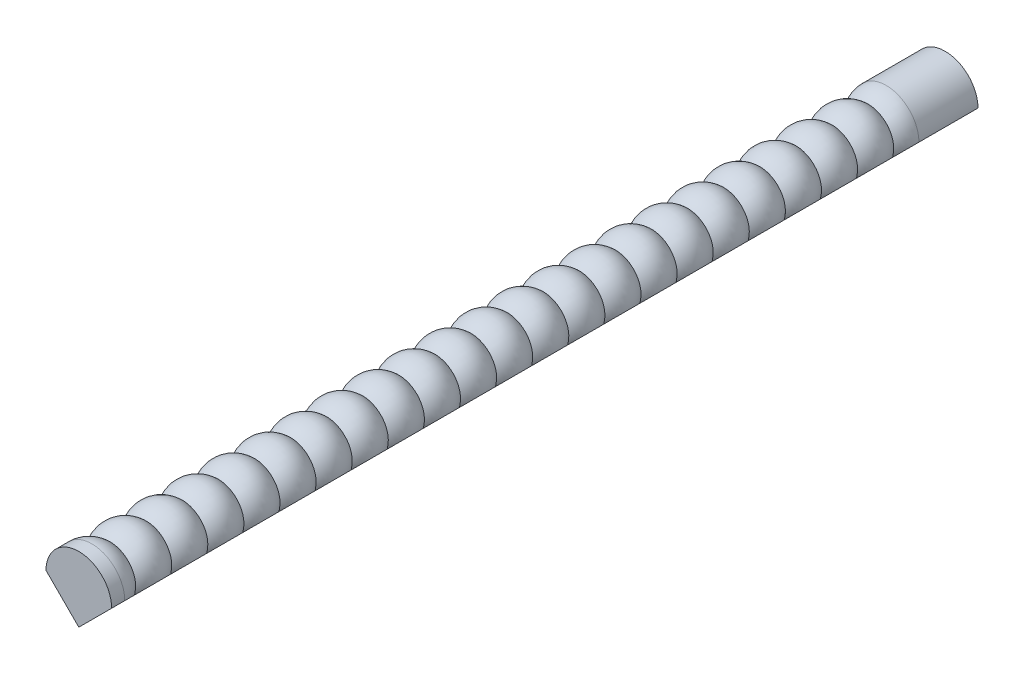
SolidWorks part; units mm, degrees
ref_plane "Front Plane" through (0, 0, 0) normal (0, 0, 1) x (1, 0, 0)
ref_plane "Top Plane" through (0, 0, 0) normal (0, 1, 0) x (1, 0, 0)
ref_plane "Right Plane" through (0, 0, 0) normal (1, 0, 0) x (0, 0, -1)
sketch "Sketch1" plane through (0, 0, 0) normal (1, 0, 0) x (0, 0, -1)
  line L0 (0, 0) -> (0, 5)
  line L1 (0, 5) -> (2, 5)
  line L2 (0, 0) -> (2, 0)
  line L3 (2, 0) -> (2, 1)
  line L4 (2, 1) -> (2, 3)
  line L5 (4, 1) -> (4.75, 1)
  line L6 (9.5, 1) -> (10.25, 1)
  line L7 (4.75, 1) -> (4.75, 3.9047) construction
  line L8 (10.25, 1) -> (10.25, 3.9047) construction
  line L9 (4.75, 1) -> (5.5, 1)
  line L10 (15, 1) -> (15.75, 1)
  line L11 (10.25, 1) -> (11, 1)
  line L12 (20.5, 1) -> (21.25, 1)
  line L13 (15.75, 1) -> (16.5, 1)
  line L14 (26, 1) -> (26.75, 1)
  line L15 (21.25, 1) -> (22, 1)
  line L16 (31.5, 1) -> (32.25, 1)
  line L17 (26.75, 1) -> (27.5, 1)
  line L18 (37, 1) -> (37.75, 1)
  line L19 (32.25, 1) -> (33, 1)
  line L20 (42.5, 1) -> (43.25, 1)
  line L21 (37.75, 1) -> (38.5, 1)
  line L22 (48, 1) -> (48.75, 1)
  line L23 (43.25, 1) -> (44, 1)
  line L24 (53.5, 1) -> (54.25, 1)
  line L25 (48.75, 1) -> (49.5, 1)
  line L26 (59, 1) -> (59.75, 1)
  line L27 (54.25, 1) -> (55, 1)
  line L28 (64.5, 1) -> (65.25, 1)
  line L29 (59.75, 1) -> (60.5, 1)
  line L30 (70, 1) -> (70.75, 1)
  line L31 (65.25, 1) -> (66, 1)
  line L32 (75.5, 1) -> (76.25, 1)
  line L33 (70.75, 1) -> (71.5, 1)
  line L34 (81, 1) -> (81.75, 1)
  line L35 (76.25, 1) -> (77, 1)
  line L36 (86.5, 1) -> (87.25, 1)
  line L37 (81.75, 1) -> (82.5, 1)
  line L38 (92, 1) -> (92.75, 1)
  line L39 (87.25, 1) -> (88, 1)
  line L40 (97.5, 1) -> (98.25, 1)
  line L41 (92.75, 1) -> (93.5, 1)
  line L42 (103, 1) -> (103.75, 1)
  line L43 (98.25, 1) -> (99, 1)
  line L44 (108.5, 1) -> (109.25, 1)
  line L45 (103.75, 1) -> (104.5, 1)
  line L46 (114, 1) -> (114.75, 1)
  line L47 (109.25, 1) -> (110, 1)
  line L48 (119.5, 1) -> (120.25, 1)
  line L49 (114.75, 1) -> (115.5, 1)
  line L50 (4.75, 3.9047) -> (10.25, 3.9047) construction
  line L51 (120.25, 1) -> (121, 1)
  line L52 (123, 3) -> (123, 1)
  line L53 (123, 1) -> (132, 1)
  line L54 (132, 1) -> (132, 5)
  line L55 (132, 5) -> (123, 5)
  arc A0 (2, 3) -> (4, 1) centre (2, 1) cw
  arc A1 (5.5, 1) -> (9.5, 1) centre (7.5, 1) cw
  arc A2 (4.75, 3.9047) -> (10.25, 3.9047) centre (7.5, 1) cw
  arc A3 (2, 5) -> (4.75, 3.9047) centre (2, 1) cw
  arc A4 (10.25, 3.9047) -> (15.75, 3.9047) centre (13, 1) cw
  arc A5 (11, 1) -> (15, 1) centre (13, 1) cw
  arc A6 (15.75, 3.9047) -> (21.25, 3.9047) centre (18.5, 1) cw
  arc A7 (16.5, 1) -> (20.5, 1) centre (18.5, 1) cw
  arc A8 (21.25, 3.9047) -> (26.75, 3.9047) centre (24, 1) cw
  arc A9 (22, 1) -> (26, 1) centre (24, 1) cw
  arc A10 (26.75, 3.9047) -> (32.25, 3.9047) centre (29.5, 1) cw
  arc A11 (27.5, 1) -> (31.5, 1) centre (29.5, 1) cw
  arc A12 (32.25, 3.9047) -> (37.75, 3.9047) centre (35, 1) cw
  arc A13 (33, 1) -> (37, 1) centre (35, 1) cw
  arc A14 (37.75, 3.9047) -> (43.25, 3.9047) centre (40.5, 1) cw
  arc A15 (38.5, 1) -> (42.5, 1) centre (40.5, 1) cw
  arc A16 (43.25, 3.9047) -> (48.75, 3.9047) centre (46, 1) cw
  arc A17 (44, 1) -> (48, 1) centre (46, 1) cw
  arc A18 (48.75, 3.9047) -> (54.25, 3.9047) centre (51.5, 1) cw
  arc A19 (49.5, 1) -> (53.5, 1) centre (51.5, 1) cw
  arc A20 (54.25, 3.9047) -> (59.75, 3.9047) centre (57, 1) cw
  arc A21 (55, 1) -> (59, 1) centre (57, 1) cw
  arc A22 (59.75, 3.9047) -> (65.25, 3.9047) centre (62.5, 1) cw
  arc A23 (60.5, 1) -> (64.5, 1) centre (62.5, 1) cw
  arc A24 (65.25, 3.9047) -> (70.75, 3.9047) centre (68, 1) cw
  arc A25 (66, 1) -> (70, 1) centre (68, 1) cw
  arc A26 (70.75, 3.9047) -> (76.25, 3.9047) centre (73.5, 1) cw
  arc A27 (71.5, 1) -> (75.5, 1) centre (73.5, 1) cw
  arc A28 (76.25, 3.9047) -> (81.75, 3.9047) centre (79, 1) cw
  arc A29 (77, 1) -> (81, 1) centre (79, 1) cw
  arc A30 (81.75, 3.9047) -> (87.25, 3.9047) centre (84.5, 1) cw
  arc A31 (82.5, 1) -> (86.5, 1) centre (84.5, 1) cw
  arc A32 (87.25, 3.9047) -> (92.75, 3.9047) centre (90, 1) cw
  arc A33 (88, 1) -> (92, 1) centre (90, 1) cw
  arc A34 (92.75, 3.9047) -> (98.25, 3.9047) centre (95.5, 1) cw
  arc A35 (93.5, 1) -> (97.5, 1) centre (95.5, 1) cw
  arc A36 (98.25, 3.9047) -> (103.75, 3.9047) centre (101, 1) cw
  arc A37 (99, 1) -> (103, 1) centre (101, 1) cw
  arc A38 (103.75, 3.9047) -> (109.25, 3.9047) centre (106.5, 1) cw
  arc A39 (104.5, 1) -> (108.5, 1) centre (106.5, 1) cw
  arc A40 (109.25, 3.9047) -> (114.75, 3.9047) centre (112, 1) cw
  arc A41 (110, 1) -> (114, 1) centre (112, 1) cw
  arc A42 (114.75, 3.9047) -> (120.25, 3.9047) centre (117.5, 1) cw
  arc A43 (115.5, 1) -> (119.5, 1) centre (117.5, 1) cw
  arc A44 (121, 1) -> (123, 3) centre (123, 1) cw
  arc A45 (120.25, 3.9047) -> (123, 5) centre (123, 1) cw
  dimension "D5" = 1.5
  dimension "D6" = 2
  dimension "D11" = 2
  dimension "D14" = 4
  dimension "D15" = 4
  dimension "D1" = 5
  dimension "D2" = 2
  dimension "D3" = 1
  dimension "D4" = 2
  dimension "D7" = 0.75
  dimension "D9" = 5.5
  dimension "D10" = 0.75
  dimension "D12" = 9
  dimension "D13" = 9
  dimension "D8" = 21
revolve "Revolve1" add sketch "Sketch1" angle 360 about L2
sketch "Sketch2" plane through (0, 0, -132) normal (0, 0, -1) x (-1, 0, 0)
  line L0 (-5, 0) -> (0, 0)
  line L1 (0, 0) -> (5, 0)
  line L2 (0, 0) -> (0, -5)
  line L3 (0, -5) -> (-5, 0)
  line L4 (0, -5) -> (5, 0)
  circle A0 centre (0, 0) radius 5
  circle M6 centre (0, 0) radius 5
  dimension "D1" = 10
extrude "Cut-Extrude3" cut sketch "Sketch2" against normal blind 140 contours L3 M6 | L4 M6 | A0
